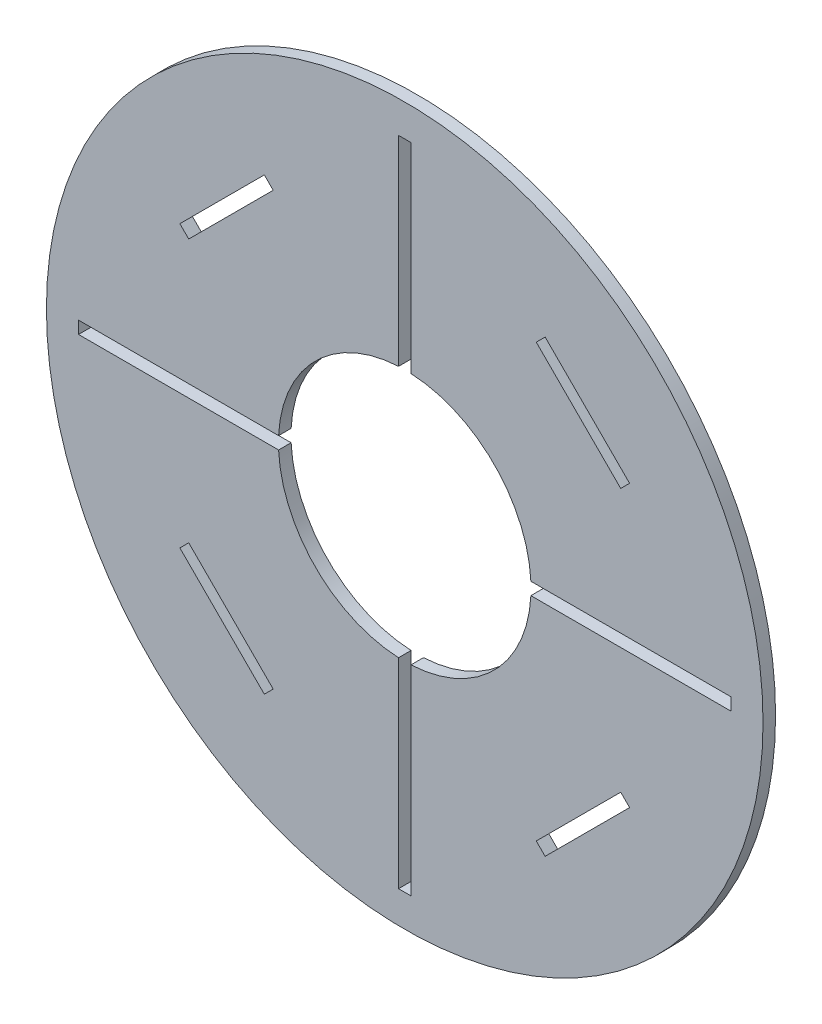
SolidWorks part; units mm, degrees
material "Pine"
ref_plane "Front Plane" through (0, 0, 0) normal (0, 0, 1) x (1, 0, 0)
ref_plane "Top Plane" through (0, 0, 0) normal (0, 1, 0) x (1, 0, 0)
ref_plane "Right Plane" through (0, 0, 0) normal (1, 0, 0) x (0, 0, -1)
sketch "Sketch1" plane through (0, 0, 0) normal (0, 0, 1) x (1, 0, 0)
  circle A0 centre (0, 0) radius 152.4
  circle A1 centre (0, 0) radius 53.721
  dimension "D1" = 107.442
  dimension "D2" = 304.8
extrude "Boss-Extrude1" add sketch "Sketch1" along normal blind 5.334
sketch "Sketch2" plane through (0, 0, 5.334) normal (0, 0, 1) x (1, 0, 0)
  line L0 (0, 53.721) -> (0, 138.746) construction
  line L1 (-2.6416, 53.656) -> (-2.6416, 138.746)
  line L2 (-2.6416, 138.746) -> (2.6416, 138.746)
  line L3 (2.6416, 138.746) -> (2.6416, 53.656)
  circle A0 centre (0, 0) radius 53.721 construction
  arc A3 (2.6416, 53.656) -> (-2.6416, 53.656) centre (0, 0) ccw
  point P11 (5.9181, 118.3674)
  dimension "D2" = 85.09
  dimension "D3" = 5.2832
extrude "Cut-Extrude2" cut sketch "Sketch2" against normal up to next
pattern_circular "CirPattern1" count 4 over 360 about axis through (0, 0, 0) along (0, 0, 1) of "Cut-Extrude2"
sketch "Sketch3" plane through (0, 0, 5.334) normal (0, 0, 1) x (1, 0, 0)
  line L0 (0, 0) -> (-107.7631, 107.7631) construction
  line L1 (-95.6397, 59.7187) -> (-59.7187, 95.6397)
  line L2 (-95.6397, 59.7187) -> (-91.868, 55.947)
  line L3 (-91.868, 55.947) -> (-55.947, 91.868)
  line L4 (-55.947, 91.868) -> (-59.7187, 95.6397)
  circle A0 centre (0, 0) radius 152.4 construction
  arc A1 (-2.6416, 53.656) -> (-53.656, 2.6416) centre (0, 0) ccw construction
  point P8 (-73.9075, 73.9075)
  point P10 (0, 0)
  point P11 (-37.9865, 37.9865)
  dimension "D1" = 45
  dimension "D2" = 5.334
  dimension "D3" = 50.8
  dimension "D4" = 50.8
extrude "Cut-Extrude3" cut sketch "Sketch3" against normal up to next
pattern_circular "CirPattern2" count 4 over 360 about axis through (0, 0, 0) along (0, 0, 1) of "Cut-Extrude3"
